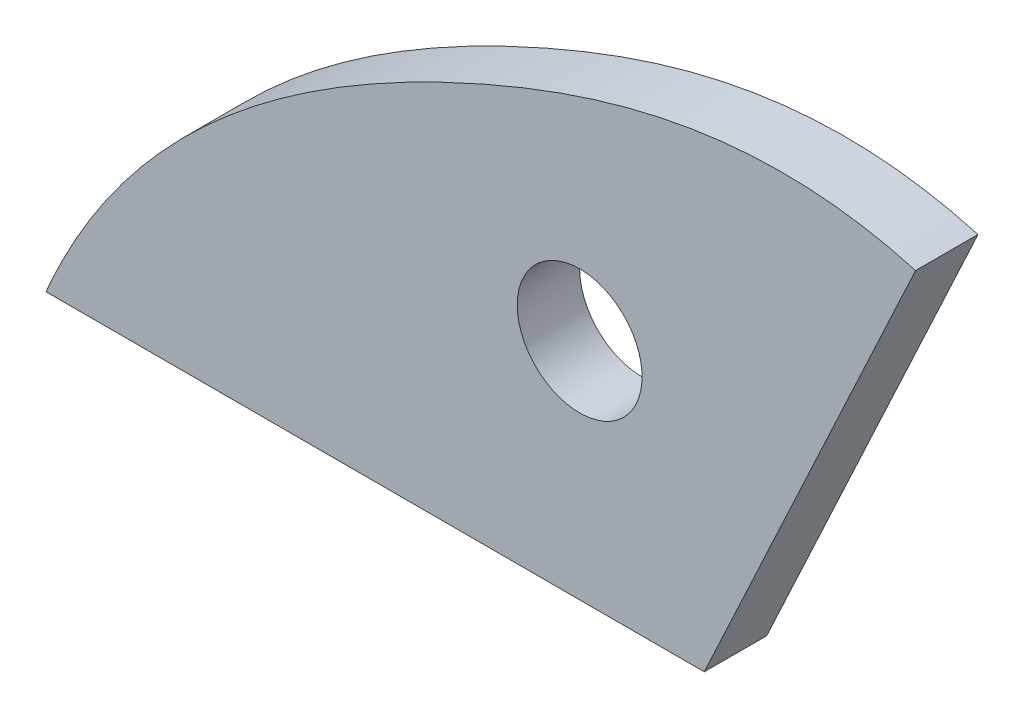
SolidWorks part; units mm, degrees
ref_plane "Front Plane" through (0, 0, 0) normal (0, 0, 1) x (1, 0, 0)
ref_plane "Top Plane" through (0, 0, 0) normal (0, 1, 0) x (1, 0, 0)
ref_plane "Right Plane" through (0, 0, 0) normal (1, 0, 0) x (0, 0, -1)
sketch "Sketch1" plane through (0, 0, 0) normal (0, 0, 1) x (1, 0, 0)
  line L0 (0, 0) -> (803.656, 0)
  line L1 (803.656, 0) -> (1061.6402, 553.2488)
  line L2 (803.656, 0) -> (1107.8553, 0) construction
  circle A0 centre (651.5375, 273.8413) radius 76.2
  spline S0 degree 3 poles (1061.6402, 553.2488) (874.0289, 606.5899) (453.4296, 493.3577) (100.6837, 235.6194) (0, 0) knots 0 0 0 0 0.433791 1 1 1 1
  dimension "D2" = 65
  dimension "D1" = 803.656
extrude "Boss-Extrude1" add sketch "Sketch1" along normal blind 76.2
